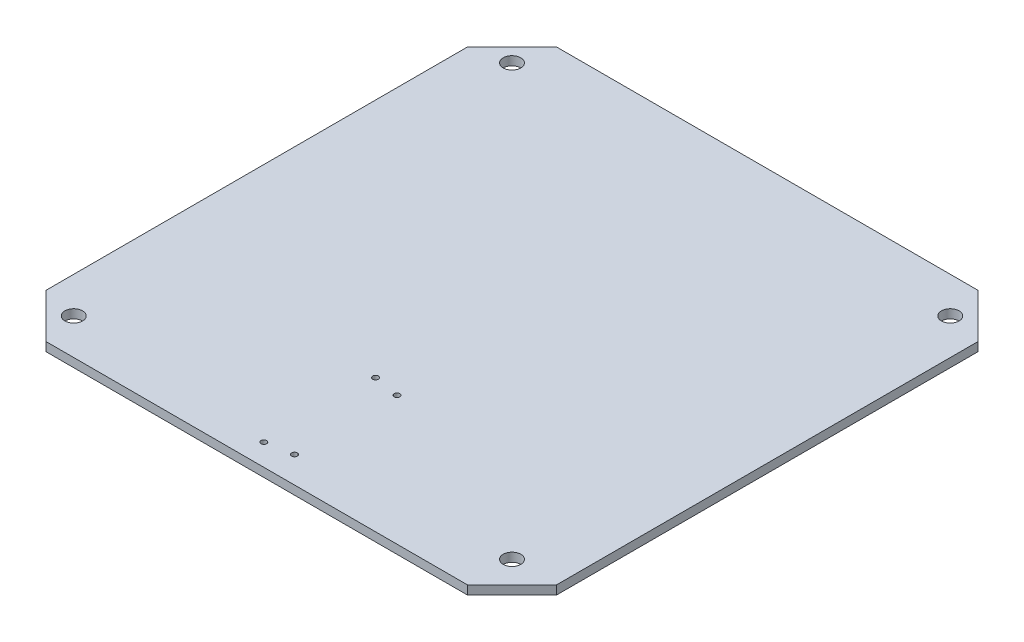
SolidWorks part; units mm, degrees
material "A-Glass Fiber"
ref_plane "Front Plane" through (0, 0, 0) normal (0, 0, 1) x (1, 0, 0)
ref_plane "Top Plane" through (0, 0, 0) normal (0, 1, 0) x (1, 0, 0)
ref_plane "Right Plane" through (0, 0, 0) normal (1, 0, 0) x (0, 0, -1)
sketch "Sketch1" plane through (0, 0, 0) normal (0, 1, 0) x (1, 0, 0)
  line L0 (-46, 38) -> (-38, 46)
  line L1 (-38, -46) -> (38, -46)
  line L2 (-46, -38) -> (-46, 38)
  line L3 (-38, 46) -> (38, 46)
  line L4 (46, -38) -> (46, 38)
  line L5 (-42, -42) -> (42, 42) construction
  line L6 (-42, 42) -> (42, -42) construction
  line L7 (38, 46) -> (46, 38)
  line L8 (46, -38) -> (38, -46)
  line L9 (-46, -38) -> (-38, -46)
  point P0 (0, 0)
  dimension "D1" = 92
  dimension "D2" = 92
  dimension "D3" = 8
  dimension "D4" = 8
  dimension "D5" = 8
  dimension "D6" = 8
  dimension "D7" = 8
  dimension "D8" = 46
  dimension "D9" = 46
extrude "Boss-Extrude1" add sketch "Sketch1" along normal blind 1.59 contours L2 L0 L3 L7 L4 L8 L1 L9
sketch "Sketch2" plane through (0, 1.59, 0) normal (0, 1, 0) x (1, 0, 0)
  line L0 (46, -38) -> (46, 38) construction
  line L1 (-47.5, -47.5) -> (47.5, -47.5) construction
  line L2 (-47.5, -47.5) -> (-47.5, 47.5) construction
  line L3 (-47.5, 47.5) -> (47.5, 47.5) construction
  line L4 (47.5, -47.5) -> (47.5, 47.5) construction
  line L5 (-47.5, -47.5) -> (47.5, 47.5) construction
  line L6 (-47.5, 47.5) -> (47.5, -47.5) construction
  circle A0 centre (-39.5, 39.5) radius 1.59
  circle A1 centre (39.5, 39.5) radius 1.59
  circle A2 centre (38, -38) radius 1.59
  circle A3 centre (-39.5, -39.5) radius 1.59
  circle A4 centre (-2.67, -21.93) radius 0.51
  circle A5 centre (2.03, -22.75) radius 0.51
  circle A6 centre (-2.67, -42.07) radius 0.51
  circle A7 centre (2.03, -41.24) radius 0.51
  point P0 (0, 0)
  point P24 (0, 0)
  point P25 (0, 0)
  point P26 (0, 0)
  dimension "D3" = 3.18
  dimension "D8" = 1.02
  dimension "D1" = 95
  dimension "D2" = 95
  dimension "D4" = 8
  dimension "D5" = 8
  dimension "D6" = 8
  dimension "D7" = 8
  dimension "D9" = 5.43
  dimension "D10" = 6.26
  dimension "D11" = 25.57
  dimension "D12" = 24.75
  dimension "D13" = 44.83
  dimension "D14" = 49.53
extrude "Cut-Extrude1" cut sketch "Sketch2" against normal blind 1.59
